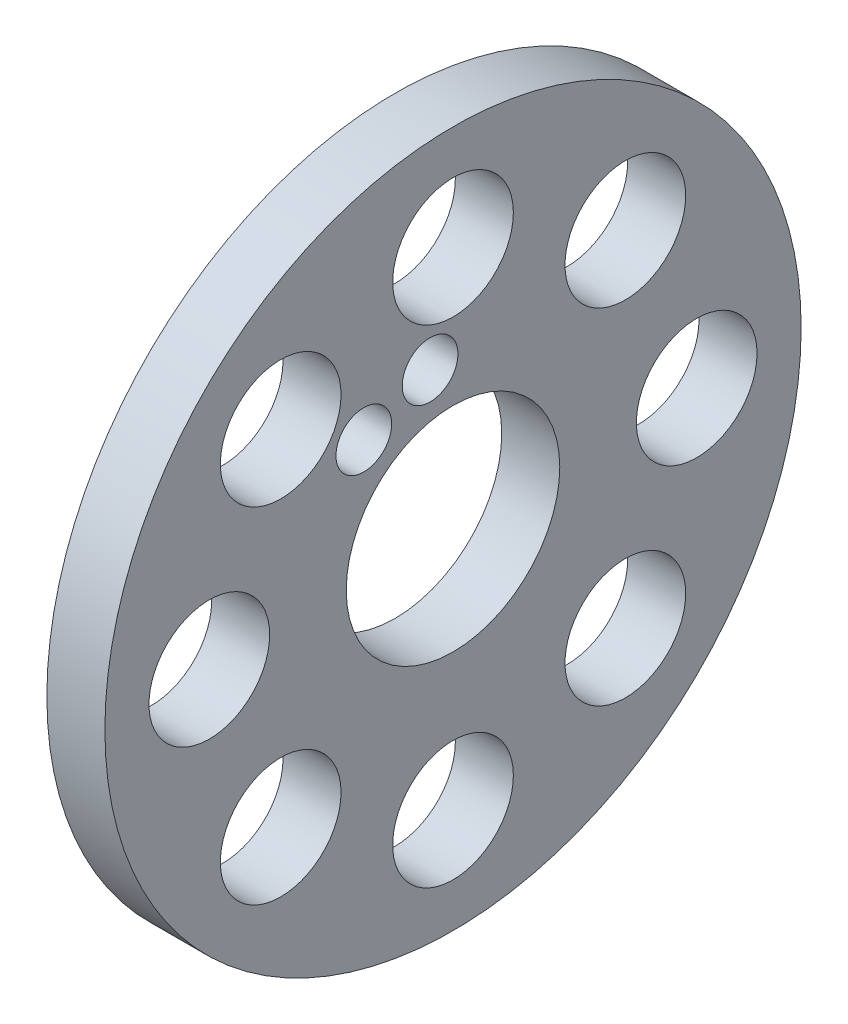
SolidWorks part; units mm, degrees
ref_plane "Front Plane" through (0, 0, 0) normal (0, 0, 1) x (1, 0, 0)
ref_plane "Top Plane" through (0, 0, 0) normal (0, 1, 0) x (1, 0, 0)
ref_plane "Right Plane" through (0, 0, 0) normal (1, 0, 0) x (0, 0, -1)
sketch "Axial profile (mm)" plane through (0, 0, 0) normal (0, 0, 1) x (1, 0, 0)
  line L0 (-110, 0) -> (75, 0) construction
  line L1 (143.7, 9.2) -> (148.7, 9.2)
  line L2 (148.7, 9.2) -> (148.7, 30)
  line L3 (148.7, 30) -> (143.7, 30)
  line L4 (143.7, 30) -> (143.7, 9.2)
revolve "Full revolution" add sketch "Axial profile (mm)" angle 360 about L0
sketch "Sketch2" plane through (0, 0, 0) normal (1, 0, 0) x (0, 0, -1)
  circle A0 centre (0, 21) radius 5.2
  circle A1 centre (-14.8492, 14.8492) radius 5.2
  circle A2 centre (-21, 0) radius 5.2
  circle A3 centre (-14.8492, -14.8492) radius 5.2
  circle A4 centre (0, -21) radius 5.2
  circle A5 centre (14.8492, -14.8492) radius 5.2
  circle A6 centre (21, 0) radius 5.2
  circle A7 centre (14.8492, 14.8492) radius 5.2
  circle A8 centre (-1.9774, 12.8487) radius 2.4
  circle A9 centre (-7.6872, 10.4836) radius 2.4
extrude "Axial holes" cut sketch "Sketch2" against normal through all and the other way through all
